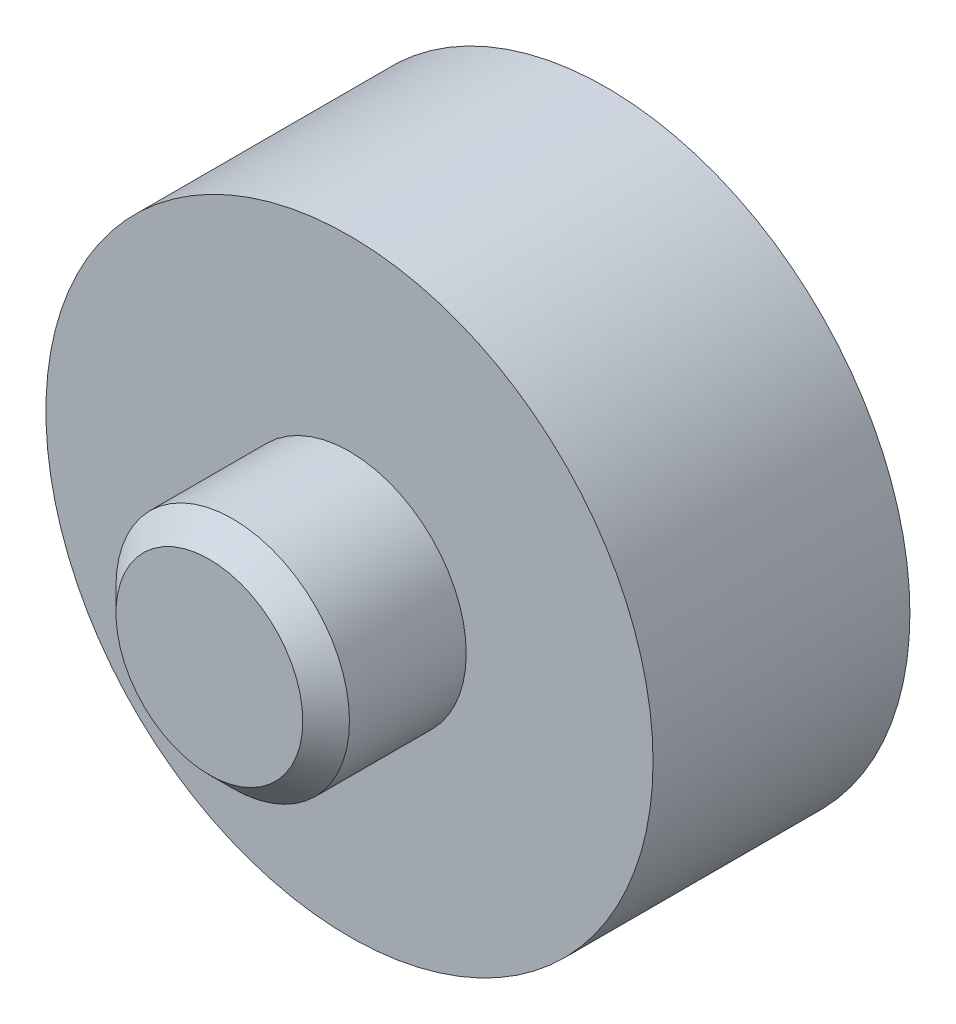
SolidWorks part; units mm, degrees
ref_plane "Plan de face" through (0, 0, 0) normal (0, 0, 1) x (1, 0, 0)
ref_plane "Plan de dessus" through (0, 0, 0) normal (0, 1, 0) x (1, 0, 0)
ref_plane "Plan de droite" through (0, 0, 0) normal (1, 0, 0) x (0, 0, -1)
sketch "Esquisse1" plane through (0, 0, 0) normal (0, 0, 1) x (1, 0, 0)
  circle A0 centre (0, 0) radius 2.75
  circle A1 centre (0, 0) radius 6.5
  dimension "D1" = 5.5
  dimension "D2" = 13
extrude "Boss.-Extru.1" add sketch "Esquisse1" along normal blind 3.5
sketch "Esquisse2" plane through (0, 0, 3.5) normal (0, 0, 1) x (1, 0, 0)
  circle A1 centre (0, 0) radius 6.5
extrude "Boss.-Extru.2" add sketch "Esquisse2" along normal blind 2
sketch "Esquisse3" plane through (0, 0, 5.5) normal (0, 0, 1) x (1, 0, 0)
  circle A0 centre (0, 0) radius 2.5
  dimension "D1" = 5
extrude "Boss.-Extru.3" add sketch "Esquisse3" along normal blind 3
chamfer "Chanfrein1" distance 0.5 angle 45 1 edges at (2.5, 0, 8.5)
